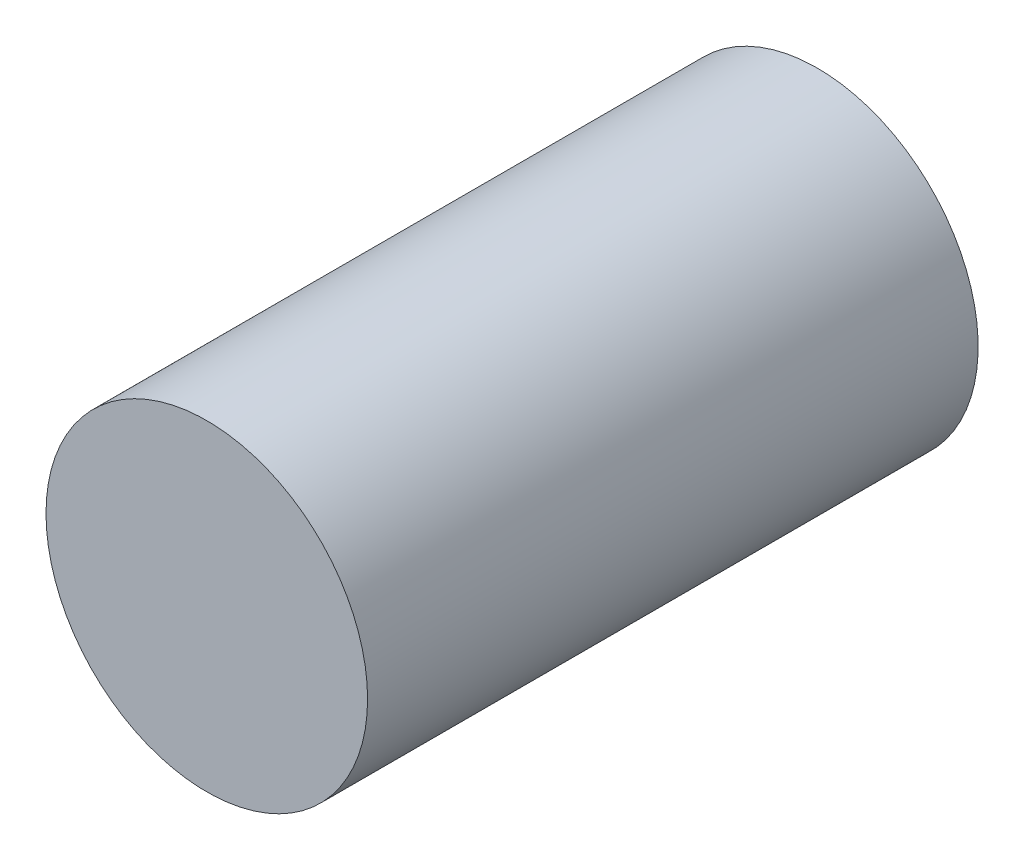
SolidWorks part; units mm, degrees
material "PMMA"
ref_plane "Plan de face" through (0, 0, 0) normal (0, 0, 1) x (1, 0, 0)
ref_plane "Plan de dessus" through (0, 0, 0) normal (0, 1, 0) x (1, 0, 0)
ref_plane "Plan de droite" through (0, 0, 0) normal (1, 0, 0) x (0, 0, -1)
ref_plane "Plan1" through (0, 0, 0) normal (0, -1, 0) x (1, 0, 0)
sketch "Esquisse1" plane through (0, 0, 0) normal (0, -1, 0) x (1, 0, 0)
  line L0 (82.55, -149.225) -> (82.55, 149.225)
  line L1 (82.55, 149.225) -> (76.2, 149.225)
  line L2 (76.2, 149.225) -> (76.2, -149.225)
  line L3 (76.2, -149.225) -> (82.55, -149.225)
  line L4 (0, 149.225) -> (0, -149.225) construction
revolve "Révolution1" add sketch "Esquisse1" angle 360 about L4
sketch "Esquisse2" plane through (0, 0, 149.225) normal (0, 0, 1) x (1, 0, 0)
  circle A0 centre (0, 0) radius 82.55
  circle A1 centre (0, 0) radius 82.55 construction
extrude "Boss.-Extru.1" add sketch "Esquisse2" along normal blind 15
